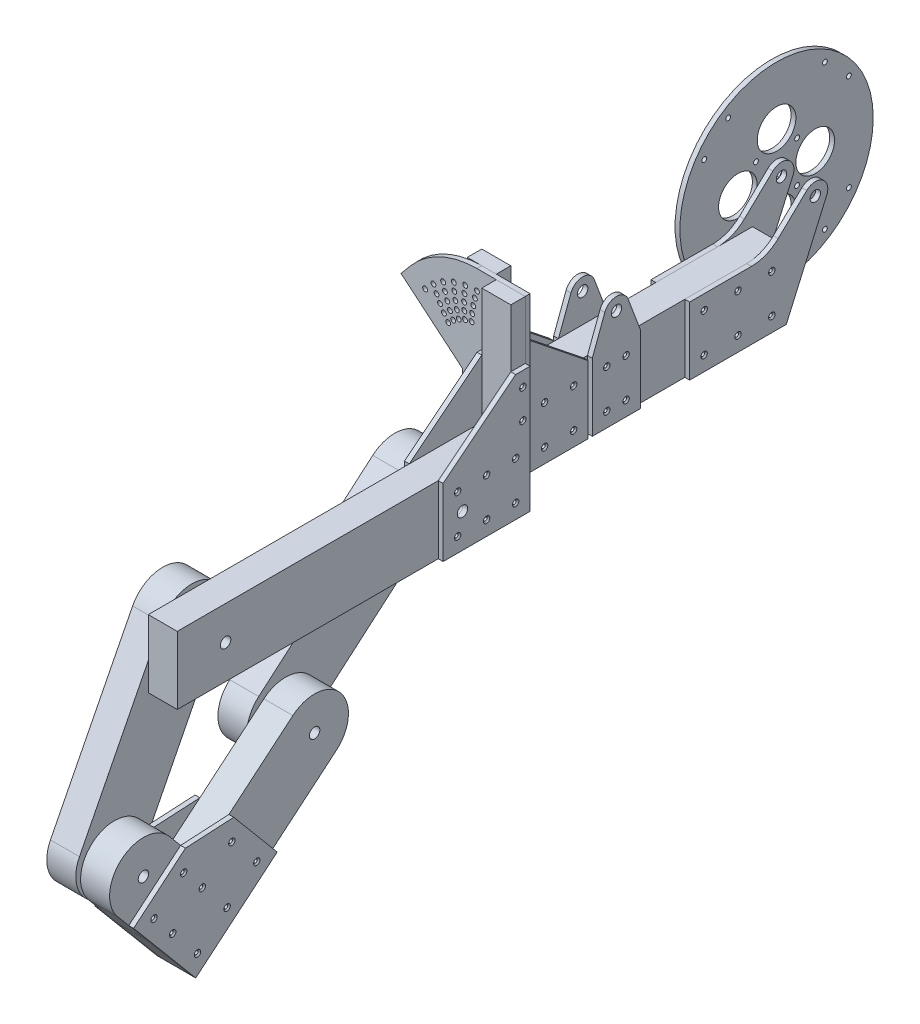
SolidWorks part; units mm, degrees
material "6061-T6 (SS)"
ref_plane "Front Plane" through (0, 0, 0) normal (0, 0, 1) x (1, 0, 0)
ref_plane "Top Plane" through (0, 0, 0) normal (0, 1, 0) x (1, 0, 0)
ref_plane "Right Plane" through (0, 0, 0) normal (1, 0, 0) x (0, 0, -1)
sketch "Sketch1" plane through (0, 0, 0) normal (1, 0, 0) x (0, 0, -1)
  line L1 (7.1857, 0) -> (3.5929, 6.223)
  line L2 (3.5929, 6.223) -> (-3.5929, 6.223)
  line L3 (-3.5929, 6.223) -> (-7.1857, 0)
  line L4 (-7.1857, 0) -> (-3.5929, -6.223)
  line L5 (-3.5929, -6.223) -> (3.5929, -6.223)
  line L6 (3.5929, -6.223) -> (7.1857, 0)
  circle A0 centre (0, 0) radius 127
  circle A2 centre (0, 50.8) radius 25.4
  circle A3 centre (50.8, 0) radius 25.4
  circle A4 centre (0, -50.8) radius 25.4
  circle A5 centre (-50.8, 0) radius 25.4
  circle A7 centre (0, 0) radius 203.2 construction
  circle A8 centre (0, 0) radius 6.223 construction
  point P14 (0, 0)
  dimension "D1" = 254
  dimension "D2" = 25.4
  dimension "D3" = 4
  dimension "2" = 50.8
  dimension "D4" = 12.446
  dimension "D5" = 406.4
extrude "Boss-Extrude1" add sketch "Sketch1" along normal blind 6.35
sketch "Sketch3" plane through (6.35, 0, 0) normal (1, 0, 0) x (0, 0, -1)
  line L0 (-26.9408, -26.9408) -> (26.9408, 26.9408) construction
  line L1 (-26.9408, 26.9408) -> (26.9408, -26.9408) construction
  line L2 (-63.5, 95.0381) -> (0, 0) construction
  line L3 (0, 0) -> (63.5, 95.0381) construction
  circle A0 centre (-26.9408, 26.9408) radius 3.175
  circle A1 centre (26.9408, 26.9408) radius 3.175
  circle A2 centre (26.9408, -26.9408) radius 3.175
  circle A3 centre (-26.9408, -26.9408) radius 3.175
  circle A4 centre (-63.5, 95.0381) radius 3.175
  circle A5 centre (63.5, 95.0381) radius 3.175
  circle A6 centre (95.0381, 63.5) radius 3.175
  circle A7 centre (95.0381, -63.5) radius 3.175
  circle A8 centre (63.5, -95.0381) radius 3.175
  circle A9 centre (-63.5, -95.0381) radius 3.175
  circle A10 centre (-95.0381, -63.5) radius 3.175
  circle A11 centre (-95.0381, 63.5) radius 3.175
  point P29 (0, 0)
  dimension "D1" = 6.35
  dimension "D2" = 76.2
  dimension "D3" = 127
  dimension "D4" = 114.3
  dimension "D5" = 4
extrude "Cut-Extrude1" cut sketch "Sketch3" against normal blind 6.35
ref_plane "Plane1" through (6.477, 0, 0) normal (1, 0, 0) x (0, 0, -1)
sketch "Sketch4" plane through (6.477, 0, 0) normal (1, 0, 0) x (0, 0, -1)
  line L0 (-38.1, -127) -> (-165.1, -127)
  line L1 (-38.1, -38.1) -> (-235.8684, -38.1) construction
  line L2 (-38.1, -38.1) -> (-38.1, -127) construction
  line L3 (-38.1, -127) -> (-235.8684, -127) construction
  line L5 (-165.1, -127) -> (-165.1, -38.1)
  line L6 (-165.1, -38.1) -> (-83.89, -38.1)
  line L7 (-48.7683, -24.0029) -> (-11.3212, 11.8309)
  line L8 (-38.1, -127) -> (14.9832, -6.6063)
  circle A0 centre (0, 0) radius 6.85
  arc A1 (14.9832, -6.6063) -> (-11.3212, 11.8309) centre (0, 0) ccw
  arc A2 (-83.89, -38.1) -> (-48.7683, -24.0029) centre (-83.89, 12.7) ccw
  point P18 (-63.5, -38.1)
  dimension "D1" = 13.7
  dimension "D5" = 9.525
  dimension "D8" = 50.8
  dimension "D2" = 127
  dimension "D3" = 38.1
  dimension "D4" = 38.1
  dimension "D6" = 101.6
  dimension "D7" = 88.9
extrude "Boss-Extrude2" add sketch "Sketch4" along normal blind 6.35 separate body
ref_plane "Plane2" through (0, 0, 38.1) normal (0, 0, 1) x (1, 0, 0)
sketch "Sketch7" plane through (0, 0, 38.1) normal (0, 0, 1) x (1, 0, 0)
  line L1 (12.827, -127) -> (50.927, -127)
  line L2 (12.827, -127) -> (12.827, -38.1)
  line L3 (12.827, -38.1) -> (50.927, -38.1)
  line L4 (50.927, -127) -> (50.927, -38.1)
  dimension "D1" = 38.1
extrude "Boss-Extrude3" add sketch "Sketch7" along normal blind 374.65 separate body
ref_plane "Plane3" through (31.877, 0, 0) normal (1, 0, 0) x (0, 0, -1)
hole_wizard "CSK for #8 Flat Head Machine Screw (100)5" positions "Sketch38" profile "Sketch39" countersink size "#8" standard "ANSI Inch"
sketch "Sketch38" plane through (6.477, 0, 0) normal (-1, 0, 0) x (0, 0, 1)
  line L0 (146.05, -107.95) -> (146.05, -127) construction
  line L1 (165.1, -127) -> (38.1, -127) construction
  line L3 (146.05, -107.95) -> (165.1, -107.95) construction
  line L4 (165.1, -38.1) -> (165.1, -127) construction
  line L6 (57.15, -57.15) -> (57.15, -38.1) construction
  line L8 (83.89, -38.1) -> (165.1, -38.1) construction
  line L9 (57.15, -57.15) -> (38.1, -57.15) construction
  line L11 (146.05, -107.95) -> (101.6, -107.95) construction
  line L12 (101.6, -107.95) -> (57.15, -107.95) construction
  point P0 (146.05, -57.15)
  point P2 (146.05, -107.95)
  point P4 (101.6, -107.95)
  point P6 (57.15, -107.95)
  point P8 (101.6, -57.15)
  point P10 (57.15, -57.15)
  dimension "D1" = 19.05
sketch "Sketch39" plane through (6.477, -57.15, 146.05) normal (0, 1, 0) x (0, 0, 1)
  line L0 (0, 0) -> (0, 7.7007)
  line L1 (0, 7.7007) -> (2.2479, 6.35)
  line L2 (2.2479, 6.35) -> (2.2479, 1.6518)
  line L3 (2.2479, 1.6518) -> (4.2164, 0)
  line L5 (4.2164, 0) -> (0, 0)
  line L6 (-2.2479, 1.6518) -> (-4.2164, 0) construction
  line L10 (0, 7.7007) -> (-2.2479, 6.35) construction
  line L11 (0, -6.35) -> (0, 107.95) construction
  dimension "Hole Dia." = 4.4958
  dimension "Hole Depth" = 6.35
  dimension "Near C'Sink Dia." = 8.4328
  dimension "Near C'Sink Angle" = 100
  dimension "Drill Angle" = 118
mirror "Mirror1" about plane through (31.877, 0, 0) normal (1, 0, 0) of bodies 131 104
sketch "Sketch8" plane through (0, -38.1, 0) normal (0, 1, 0) x (1, 0, 0)
  line L0 (12.827, -412.75) -> (12.827, -38.1) construction
  line L1 (50.927, -412.75) -> (12.827, -412.75)
  line L2 (50.927, -412.75) -> (50.927, -393.7)
  line L3 (50.927, -393.7) -> (12.827, -393.7)
  line L4 (12.827, -412.75) -> (12.827, -393.7)
  dimension "D1" = 19.05
extrude "Boss-Extrude4" add sketch "Sketch8" along normal blind 152.4 separate body
sketch "Sketch9" plane through (12.827, 0, 0) normal (-1, 0, 0) x (0, 0, 1)
  line L0 (412.75, 38.1) -> (412.75, -127)
  line L1 (412.75, 114.3) -> (412.75, -38.1) construction
  line L2 (412.75, -127) -> (298.45, -127)
  line L3 (298.45, -127) -> (298.45, -38.1)
  line L4 (412.75, -38.1) -> (38.1, -38.1) construction
  line L5 (298.45, -38.1) -> (393.7, 38.1)
  line L6 (393.7, 114.3) -> (393.7, -38.1) construction
  line L7 (393.7, 38.1) -> (412.75, 38.1)
  dimension "D1" = 114.3
extrude "Boss-Extrude5" add sketch "Sketch9" along normal blind 6.35 separate body
hole_wizard "CSK for #8 Flat Head Machine Screw (100)1" positions "Sketch12" profile "Sketch11" countersink size "#8" standard "ANSI Inch"
sketch "Sketch12" plane through (6.477, 0, 0) normal (-1, 0, 0) x (0, 0, 1)
  line L0 (403.225, -19.05) -> (403.225, 19.05) construction
  line L2 (393.7, 19.05) -> (412.75, 19.05) construction
  line L4 (412.75, 114.3) -> (412.75, -38.1) construction
  line L5 (393.7, 114.3) -> (393.7, -38.1) construction
  line L6 (403.225, 19.05) -> (403.225, 38.1) construction
  line L7 (412.75, 38.1) -> (393.7, 38.1) construction
  line L9 (393.7, -107.95) -> (393.7, -57.15) construction
  line L10 (393.7, -57.15) -> (355.6, -57.15) construction
  line L11 (355.6, -57.15) -> (317.5, -57.15) construction
  line L13 (355.6, -57.15) -> (355.6, -107.95) construction
  line L15 (317.5, -57.15) -> (317.5, -107.95) construction
  line L16 (317.5, -107.95) -> (355.6, -107.95) construction
  line L17 (355.6, -107.95) -> (393.7, -107.95) construction
  line L19 (412.75, -127) -> (412.75, 38.1) construction
  line L20 (298.45, -127) -> (412.75, -127) construction
  line L21 (393.7, -107.95) -> (393.7, -127) construction
  line L23 (393.7, -107.95) -> (412.75, -107.95) construction
  line L25 (317.5, -57.15) -> (317.5, -38.1) construction
  line L27 (412.75, -38.1) -> (38.1, -38.1) construction
  line L28 (317.5, -57.15) -> (298.45, -57.15) construction
  line L29 (298.45, -38.1) -> (298.45, -127) construction
  point P0 (403.225, 19.05)
  point P2 (403.225, -19.05)
  point P4 (393.7, -57.15)
  point P6 (393.7, -107.95)
  point P8 (355.6, -107.95)
  point P10 (355.6, -57.15)
  point P12 (317.5, -57.15)
  point P14 (317.5, -107.95)
  dimension "D1" = 19.05
  dimension "D2" = 38.1
  dimension "D3" = 19.05
  dimension "D4" = 19.05
sketch "Sketch11" plane through (6.477, 19.05, 403.225) normal (0, 1, 0) x (0, 0, 1)
  line L0 (0, 0) -> (0, 8.9453)
  line L1 (0, 8.9453) -> (2.2479, 7.5946)
  line L2 (2.2479, 7.5946) -> (2.2479, 1.6518)
  line L3 (2.2479, 1.6518) -> (4.2164, 0)
  line L5 (4.2164, 0) -> (0, 0)
  line L6 (-2.2479, 1.6518) -> (-4.2164, 0) construction
  line L10 (0, 8.9453) -> (-2.2479, 7.5946) construction
  line L11 (0, -6.35) -> (0, 107.95) construction
  dimension "Hole Dia." = 4.4958
  dimension "Hole Depth" = 7.5946
  dimension "Near C'Sink Dia." = 8.4328
  dimension "Near C'Sink Angle" = 100
  dimension "Drill Angle" = 118
mirror "Mirror2" about plane through (31.877, 0, 0) normal (1, 0, 0) of bodies 109 111
sketch "Sketch13" plane through (0, 0, 412.75) normal (0, 0, 1) x (1, 0, 0)
  line L0 (12.827, 0) -> (50.927, 0) construction
  line L1 (12.827, 114.3) -> (12.827, -38.1) construction
  line L2 (50.927, -127) -> (50.927, 38.1) construction
  circle A0 centre (31.877, 0) radius 3.175
  circle A1 centre (31.877, 88.9) radius 3.175
  dimension "D1" = 6.35
  dimension "D2" = 88.9
extrude "Cut-Extrude3" cut sketch "Sketch13" against normal up to next (19.05 mm away)
sketch "Sketch16" plane through (0, 0, 412.75) normal (0, 0, 1) x (1, 0, 0)
  line L0 (31.877, 88.9) -> (31.877, 79.375) construction
  line L1 (31.877, 79.375) -> (31.877, 69.85) construction
  line L2 (31.877, 69.85) -> (31.877, 60.325) construction
  line L3 (31.877, 60.325) -> (31.877, 50.8) construction
  circle A0 centre (31.877, 79.375) radius 3.175
  circle A1 centre (31.877, 69.85) radius 3.175
  circle A2 centre (31.877, 60.325) radius 3.175
  circle A3 centre (31.877, 50.8) radius 3.175
  circle A5 centre (31.877, 88.9) radius 3.175 construction
  dimension "D1" = 9.525
extrude "Cut-Extrude5" cut sketch "Sketch16" against normal up to next (19.05 mm away)
sketch "Sketch14" plane through (0, 0, 412.75) normal (0, 0, 1) x (1, 0, 0)
  line L1 (57.277, -38.1) -> (12.827, -38.1)
  line L2 (12.827, 114.3) -> (50.927, 114.3) construction
  line L3 (-55.6819, 73.4706) -> (31.877, 0) construction
  line L4 (31.877, 79.375) -> (31.877, 0) construction
  line L5 (31.877, 0) -> (29.1069, 79.3266) construction
  line L6 (31.877, 0) -> (29.1069, 79.3266) construction
  line L7 (31.877, 0) -> (15.374, 77.6405) construction
  line L8 (31.877, 0) -> (27.0045, 69.6798) construction
  line L9 (31.877, 69.85) -> (31.877, 0) construction
  line L10 (-21.2352, 58.9871) -> (31.877, 0) construction
  line L11 (25.5713, 59.9945) -> (31.877, 0) construction
  line L12 (31.877, 60.325) -> (31.877, 0) construction
  line L13 (24.807, 50.3056) -> (31.877, 0) construction
  line L14 (31.877, 0) -> (31.877, 50.8) construction
  line L15 (31.877, 0) -> (27.0045, 69.6798) construction
  line L16 (31.877, 0) -> (14.9788, 67.7752) construction
  line L17 (31.877, 0) -> (25.5713, 59.9945) construction
  line L18 (31.877, 0) -> (15.2492, 57.9881) construction
  line L19 (31.877, 0) -> (24.807, 50.3056) construction
  line L20 (31.877, 0) -> (16.1789, 48.3137) construction
  line L21 (31.877, 0) -> (31.877, 88.9) construction
  line L22 (31.877, 0) -> (16.4397, 87.5494) construction
  line L23 (12.827, -127) -> (12.827, 38.1) construction
  line L24 (12.827, 114.3) -> (12.827, -38.1) construction
  line L25 (31.877, 114.3) -> (50.927, 114.3)
  line L26 (-55.6819, 73.4706) -> (-67.927, 58.8775)
  line L27 (-67.927, 58.8775) -> (12.827, -8.8832)
  line L28 (12.827, -8.8832) -> (12.827, -38.1)
  line L30 (95.377, 114.3) -> (95.377, -38.1)
  line L33 (57.277, -127) -> (57.277, 38.1) construction
  line L34 (50.927, -38.1) -> (12.827, -38.1) construction
  line L35 (57.277, -38.1) -> (95.377, -38.1)
  line L37 (95.377, 114.3) -> (50.927, 114.3)
  line L39 (50.927, 114.3) -> (12.827, 114.3) construction
  line L40 (50.927, 114.3) -> (50.927, -38.1) construction
  arc A0 (31.877, 114.3) -> (-55.6819, 73.4706) centre (31.877, 0) ccw
  circle A1 centre (31.877, 0) radius 3.175 construction
  circle A2 centre (31.877, 88.9) radius 3.175
  circle A3 centre (31.877, 88.9) radius 3.175 construction
  circle A8 centre (29.1069, 79.3266) radius 3.175
  circle A9 centre (31.877, 79.375) radius 3.175 construction
  circle A10 centre (15.374, 77.6405) radius 3.175
  circle A11 centre (2.1426, 73.5952) radius 3.175
  circle A12 centre (-10.1853, 67.3138) radius 3.175
  circle A13 centre (-21.2352, 58.9871) radius 3.175
  circle A14 centre (27.0045, 69.6798) radius 3.175
  circle A15 centre (25.5713, 59.9945) radius 3.175
  circle A16 centre (24.807, 50.3056) radius 3.175
  circle A17 centre (31.877, 69.85) radius 3.175 construction
  circle A18 centre (14.9788, 67.7752) radius 3.175
  circle A19 centre (3.4664, 63.8112) radius 3.175
  circle A20 centre (-7.1826, 57.9083) radius 3.175
  circle A21 centre (-16.6449, 50.2459) radius 3.175
  circle A22 centre (15.2492, 57.9881) radius 3.175
  circle A23 centre (5.4323, 54.2198) radius 3.175
  circle A24 centre (-3.5811, 48.804) radius 3.175
  circle A25 centre (-11.5172, 41.9053) radius 3.175
  circle A26 centre (16.1789, 48.3137) radius 3.175
  circle A27 centre (8.0278, 44.8537) radius 3.175
  circle A28 centre (0.6014, 40.0309) radius 3.175
  circle A29 centre (-5.8748, 33.9918) radius 3.175
  circle A30 centre (16.4397, 87.5494) radius 3.175
  circle A31 centre (1.4714, 83.5387) radius 3.175
  circle A32 centre (-12.573, 76.9897) radius 3.175
  circle A33 centre (-25.2668, 68.1014) radius 3.175
  circle A34 centre (-36.2244, 57.1438) radius 3.175
  circle A35 centre (31.877, 0) radius 3.175
  point P28 (31.877, 0)
  dimension "D3" = 2
  dimension "D5" = 10
  dimension "D6" = 4
  dimension "D7" = 6
  dimension "D8" = 8
  dimension "D10" = 10
  dimension "D12" = 10
  dimension "D14" = 10
  dimension "D15" = 10
  dimension "D4" = 5
  dimension "D9" = 5
  dimension "D11" = 5
  dimension "D13" = 5
  dimension "D2" = 6
extrude "Boss-Extrude6" add sketch "Sketch14" along normal blind 6.35 separate body
hole_wizard "CSK for #8 Flat Head Machine Screw (100)2" positions "Sketch19" profile "Sketch20" countersink size "#8" standard "ANSI Inch"
sketch "Sketch19" plane through (0, 0, 412.75) normal (0, 0, -1) x (-1, 0, 0)
  line L0 (-95.377, -12.7) -> (-57.277, -12.7) construction
  line L1 (-95.377, -38.1) -> (-95.377, 114.3) construction
  line L2 (-57.277, -127) -> (-57.277, 38.1) construction
  line L4 (-76.327, -12.7) -> (-76.327, -38.1) construction
  line L5 (-12.827, -38.1) -> (-95.377, -38.1) construction
  line L7 (-76.327, -12.7) -> (-76.327, 12.7) construction
  line L8 (-76.327, 12.7) -> (-76.327, 38.1) construction
  line L9 (-76.327, 38.1) -> (-76.327, 63.5) construction
  line L10 (-76.327, 63.5) -> (-76.327, 88.9) construction
  line L11 (-76.327, 88.9) -> (-76.327, 114.3) construction
  line L12 (-95.377, 114.3) -> (-31.877, 114.3) construction
  point P9 (-76.327, -12.7)
  point P16 (-76.327, 12.7)
  point P17 (-76.327, 38.1)
  point P19 (-76.327, 63.5)
  point P21 (-76.327, 88.9)
sketch "Sketch20" plane through (76.327, 88.9, 412.75) normal (1, 0, 0) x (0, 1, 0)
  line L0 (0, 0) -> (0, 7.7007)
  line L1 (0, 7.7007) -> (2.2479, 6.35)
  line L2 (2.2479, 6.35) -> (2.2479, 1.6518)
  line L3 (2.2479, 1.6518) -> (4.2164, 0)
  line L5 (4.2164, 0) -> (0, 0)
  line L6 (-2.2479, 1.6518) -> (-4.2164, 0) construction
  line L10 (0, 7.7007) -> (-2.2479, 6.35) construction
  line L11 (0, -6.35) -> (0, 107.95) construction
  dimension "Hole Dia." = 4.4958
  dimension "Hole Depth" = 6.35
  dimension "Near C'Sink Dia." = 8.4328
  dimension "Near C'Sink Angle" = 100
  dimension "Drill Angle" = 118
sketch "Sketch21" plane through (0, 0, 419.1) normal (0, 0, 1) x (1, 0, 0)
  line L0 (12.827, -38.1) -> (95.377, -38.1) construction
  line L1 (95.377, 114.3) -> (57.277, 114.3)
  line L2 (95.377, 114.3) -> (95.377, -38.1)
  line L3 (95.377, -38.1) -> (57.277, -38.1)
  line L4 (57.277, 114.3) -> (57.277, -38.1)
  line L5 (12.827, -127) -> (50.927, -127) construction
extrude "Boss-Extrude7" add sketch "Sketch21" along normal blind 19.05 separate body
ref_plane "Plane4" through (0, 0, 415.925) normal (0, 0, 1) x (1, 0, 0)
sketch "Sketch23" plane through (31.877, 0, 0) normal (1, 0, 0) x (0, 0, -1)
  line L0 (-263.6019, 31.144) -> (-3.8591, 50.8544)
  line L1 (-263.6019, -31.144) -> (-3.8591, -50.8544)
  circle A0 centre (0, 0) radius 51.0007 construction
  circle A1 centre (-261.2386, 0) radius 31.2336 construction
  arc A2 (-263.6019, 31.144) -> (-263.6019, -31.144) centre (-261.2386, 0) ccw
  arc A3 (-3.8591, 50.8544) -> (-3.8591, -50.8544) centre (0, 0) cw
  dimension "D1" = 102.0013
  dimension "D2" = 62.4671
sketch "Sketch24" plane through (50.927, 0, 0) normal (1, 0, 0) x (0, 0, -1)
  line L0 (-292.9886, -127) -> (-229.4886, -127)
  line L1 (-412.75, -127) -> (-38.1, -127) construction
  line L2 (-292.9886, -127) -> (-292.9886, -38.1)
  line L3 (-412.75, -38.1) -> (-38.1, -38.1) construction
  line L4 (-292.9886, -38.1) -> (-276.574, 5.7417)
  line L5 (-245.9032, 5.7417) -> (-229.4886, -38.1)
  line L6 (-229.4886, -38.1) -> (-229.4886, -127)
  circle A0 centre (-261.2386, 0) radius 6.85
  arc A2 (-263.6019, 31.144) -> (-263.6019, -31.144) centre (-261.2386, 0) ccw construction
  circle A3 centre (-261.2386, 0) radius 16.375 construction
  arc A4 (-276.574, 5.7417) -> (-245.9032, 5.7417) centre (-261.2386, 0) cw
  point P16 (-261.2386, -127)
  dimension "D1" = 13.7
  dimension "D2" = 9.525
  dimension "2.5" = 63.5
extrude "Boss-Extrude11" add sketch "Sketch24" along normal blind 6.35 separate body
hole_wizard "CSK for #8 Flat Head Machine Screw (100)3" positions "Sketch25" profile "Sketch26" countersink size "#8" standard "ANSI Inch"
sketch "Sketch25" plane through (57.277, 0, 0) normal (1, 0, 0) x (0, 0, -1)
  line L0 (-273.9386, -57.15) -> (-273.9386, -107.95) construction
  line L1 (-273.9386, -107.95) -> (-248.5386, -107.95) construction
  line L3 (-273.9386, -107.95) -> (-273.9386, -127) construction
  line L4 (-292.9886, -127) -> (-229.4886, -127) construction
  line L6 (-273.9386, -107.95) -> (-292.9886, -107.95) construction
  line L7 (-292.9886, -38.1) -> (-292.9886, -127) construction
  line L9 (-248.5386, -57.15) -> (-248.5386, -38.1) construction
  line L11 (-248.5386, -57.15) -> (-229.4886, -57.15) construction
  line L12 (-229.4886, -127) -> (-229.4886, -38.1) construction
  line L14 (-412.75, -38.1) -> (-38.1, -38.1) construction
  point P0 (-248.5386, -57.15)
  point P2 (-248.5386, -107.95)
  point P4 (-273.9386, -107.95)
  point P6 (-273.9386, -57.15)
  dimension "D1" = 19.05
sketch "Sketch26" plane through (57.277, -57.15, 248.5386) normal (0, 1, 0) x (0, 0, -1)
  line L0 (0, 0) -> (0, 7.7007)
  line L1 (0, 7.7007) -> (2.2479, 6.35)
  line L2 (2.2479, 6.35) -> (2.2479, 1.6518)
  line L3 (2.2479, 1.6518) -> (4.2164, 0)
  line L5 (4.2164, 0) -> (0, 0)
  line L6 (-2.2479, 1.6518) -> (-4.2164, 0) construction
  line L10 (0, 7.7007) -> (-2.2479, 6.35) construction
  line L11 (0, -6.35) -> (0, 107.95) construction
  dimension "Hole Dia." = 4.4958
  dimension "Hole Depth" = 6.35
  dimension "Near C'Sink Dia." = 8.4328
  dimension "Near C'Sink Angle" = 100
  dimension "Drill Angle" = 118
mirror "Mirror4" about plane through (31.877, 0, 0) normal (1, 0, 0) of bodies 123 124
sketch "Sketch27" plane through (57.277, 0, 0) normal (-1, 0, 0) x (0, 0, 1)
  line L0 (419.1, 38.1) -> (419.1, -127)
  line L1 (419.1, 114.3) -> (419.1, -38.1) construction
  line L2 (419.1, -127) -> (533.4, -127)
  line L3 (533.4, -127) -> (533.4, -38.1)
  line L4 (533.4, -38.1) -> (438.15, 38.1)
  line L5 (438.15, 114.3) -> (438.15, -38.1) construction
  line L6 (438.15, 38.1) -> (419.1, 38.1)
  line L7 (412.75, 38.1) -> (393.7, 38.1) construction
  line L8 (298.45, -127) -> (412.75, -127) construction
  line L9 (412.75, -38.1) -> (38.1, -38.1) construction
extrude "Boss-Extrude12" add sketch "Sketch27" along normal blind 6.35 separate body
hole_wizard "CSK for #8 Flat Head Machine Screw (100)4" positions "Sketch29" profile "Sketch30" countersink size "#8" standard "ANSI Inch"
sketch "Sketch29" plane through (50.927, 0, 0) normal (-1, 0, 0) x (0, 0, 1)
  line L0 (419.1, 19.05) -> (438.15, 19.05) construction
  line L1 (419.1, 38.1) -> (419.1, -127) construction
  line L3 (438.15, 114.3) -> (438.15, -38.1) construction
  line L4 (438.15, 38.1) -> (419.1, 38.1) construction
  line L5 (438.15, -107.95) -> (438.15, -127) construction
  line L6 (419.1, -127) -> (533.4, -127) construction
  line L8 (438.15, -107.95) -> (419.1, -107.95) construction
  line L10 (514.35, -57.15) -> (533.4, -57.15) construction
  line L11 (533.4, -127) -> (533.4, -38.1) construction
  line L13 (514.35, -57.15) -> (514.35, -38.1) construction
  line L15 (438.15, -107.95) -> (476.25, -107.95) construction
  line L16 (476.25, -107.95) -> (514.35, -107.95) construction
  point P0 (428.625, 19.05)
  point P2 (428.625, -19.05)
  point P4 (438.15, -57.15)
  point P6 (438.15, -107.95)
  point P8 (476.25, -57.15)
  point P10 (476.25, -107.95)
  point P12 (514.35, -57.15)
  point P14 (514.35, -107.95)
  dimension "D1" = 19.05
  dimension "D2" = 38.1
  dimension "D3" = 19.05
sketch "Sketch30" plane through (50.927, 19.05, 428.625) normal (0, 1, 0) x (0, 0, 1)
  line L0 (0, 0) -> (0, 7.7007)
  line L1 (0, 7.7007) -> (2.2479, 6.35)
  line L2 (2.2479, 6.35) -> (2.2479, 1.6518)
  line L3 (2.2479, 1.6518) -> (4.2164, 0)
  line L5 (4.2164, 0) -> (0, 0)
  line L6 (-2.2479, 1.6518) -> (-4.2164, 0) construction
  line L10 (0, 7.7007) -> (-2.2479, 6.35) construction
  line L11 (0, -6.35) -> (0, 107.95) construction
  dimension "Hole Dia." = 4.4958
  dimension "Hole Depth" = 6.35
  dimension "Near C'Sink Dia." = 8.4328
  dimension "Near C'Sink Angle" = 100
  dimension "Drill Angle" = 118
sketch "Sketch33" plane through (0, 0, 419.1) normal (0, 0, 1) x (1, 0, 0)
  line L1 (57.277, -38.1) -> (95.377, -38.1)
  line L2 (57.277, -38.1) -> (57.277, -127)
  line L3 (57.277, -127) -> (95.377, -127)
  line L4 (95.377, -38.1) -> (95.377, -127)
  dimension "D1" = 38.1
  dimension "D2" = 88.9
extrude "Boss-Extrude13" add sketch "Sketch33" along normal blind 457.2 separate body
ref_plane "Plane5" through (76.327, 0, 0) normal (1, 0, 0) x (0, 0, -1)
mirror "Mirror5" about plane through (76.327, 0, 0) normal (1, 0, 0) of bodies 127 128
sketch "Sketch40" plane through (12.827, 0, 0) normal (-1, 0, 0) x (0, 0, 1)
  circle A0 centre (57.15, -57.15) radius 1.3891
  circle A1 centre (101.6, -57.15) radius 1.3891
  circle A2 centre (57.15, -107.95) radius 1.3891
  circle A3 centre (101.6, -107.95) radius 1.3891
  circle A4 centre (146.05, -107.95) radius 1.3891
  circle A5 centre (146.05, -57.15) radius 1.3891
  circle A6 centre (248.5386, -57.15) radius 1.3891
  circle A7 centre (248.5386, -107.95) radius 1.3891
  circle A8 centre (273.9386, -57.15) radius 1.3891
  circle A9 centre (273.9386, -107.95) radius 1.3891
  circle A10 centre (317.5, -57.15) radius 1.3891
  circle A11 centre (317.5, -107.95) radius 1.3891
  circle A12 centre (355.6, -107.95) radius 1.3891
  circle A13 centre (393.7, -57.15) radius 1.3891
  circle A14 centre (393.7, -107.95) radius 1.3891
  circle A15 centre (355.6, -57.15) radius 1.3891
  circle A16 centre (403.225, -19.05) radius 1.3891
  circle A17 centre (403.225, 19.05) radius 1.3891
  circle A18 centre (146.05, -107.95) radius 2.2479 construction
  circle A19 centre (57.15, -57.15) radius 2.2479 construction
  circle A20 centre (101.6, -107.95) radius 2.2479 construction
  dimension "D1" = 2.7781
extrude "Cut-Extrude6" cut sketch "Sketch40" against normal blind 12.7
mirror "Mirror7" about plane through (31.877, 0, 0) normal (1, 0, 0) of "Cut-Extrude6"
sketch "Sketch42" plane through (95.377, 0, 0) normal (1, 0, 0) x (0, 0, -1)
  circle A0 centre (-428.625, 19.05) radius 1.3891
  circle A1 centre (-428.625, -19.05) radius 1.3891
  circle A2 centre (-438.15, -57.15) radius 1.3891
  circle A3 centre (-438.15, -107.95) radius 1.3891
  circle A4 centre (-476.25, -107.95) radius 1.3891
  circle A5 centre (-476.25, -57.15) radius 1.3891
  circle A6 centre (-514.35, -57.15) radius 1.3891
  circle A7 centre (-514.35, -107.95) radius 1.3891
  circle A8 centre (-476.25, -107.95) radius 2.2479 construction
  dimension "D1" = 2.7781
extrude "Cut-Extrude7" cut sketch "Sketch42" against normal blind 12.7
mirror "Mirror8" about plane through (76.327, 0, 0) normal (1, 0, 0) of "Cut-Extrude7"
sketch "Sketch43" plane through (31.877, 0, 0) normal (1, 0, 0) x (0, 0, -1)
  line L0 (-476.714, -77.1417) -> (-539.286, -87.9583) construction
  line L1 (-438.15, -57.15) -> (-438.15, -107.95) construction
  circle A0 centre (-508, -82.55) radius 6.85
  point P2 (-438.15, -82.55)
  point P6 (-508, -82.55)
  dimension "D2" = 13.7
  dimension "D1" = 508
  dimension "D3" = 63.5
extrude "Cut-Extrude8" cut sketch "Sketch43" along normal through all
sketch "Sketch44" plane through (57.277, 0, 0) normal (-1, 0, 0) x (0, 0, 1)
  circle A0 centre (812.8, -82.55) radius 6.85
  circle A1 centre (508, -82.55) radius 6.85 construction
  point P3 (508, -82.55)
  dimension "D1" = 812.8
extrude "Cut-Extrude9" cut sketch "Sketch44" against normal through all
sketch "Sketch46" plane through (57.277, 0, 0) normal (-1, 0, 0) x (0, 0, 1)
  circle A0 centre (812.8, -82.55) radius 7.9375
  circle A1 centre (812.8, -82.55) radius 15.875
  dimension "D1" = 31.75
  dimension "D2" = 15.875
extrude "Boss-Extrude14" add sketch "Sketch46" along normal blind 6.35 separate body
sketch "Sketch47" plane through (50.927, 0, 0) normal (-1, 0, 0) x (0, 0, 1)
  line L0 (508, -82.55) -> (695.8783, -243.8952) construction
  line L1 (812.8, -82.55) -> (920.7384, -294.8065) construction
  line L2 (695.8783, -243.8952) -> (852.9005, -375.6525) construction
  line L3 (852.9005, -375.6525) -> (920.7384, -294.8065) construction
  line L4 (695.8783, -243.8952) -> (832.756, -243.8952) construction
  line L5 (479.0406, -116.2717) -> (666.9189, -277.6169)
  line L6 (773.1788, -102.6985) -> (881.1172, -314.955)
  line L7 (536.9594, -48.8283) -> (724.8377, -210.1734)
  line L8 (852.4212, -62.4015) -> (960.3596, -274.658)
  circle A0 centre (508, -82.55) radius 6.85
  circle A1 centre (508, -82.55) radius 6.85 construction
  circle A2 centre (695.8783, -243.8952) radius 6.85
  arc A3 (536.9594, -48.8283) -> (479.0406, -116.2717) centre (508, -82.55) ccw
  arc A4 (666.9189, -277.6169) -> (724.8377, -210.1734) centre (695.8783, -243.8952) ccw
  arc A5 (773.1788, -102.6985) -> (852.4212, -62.4015) centre (812.8, -82.55) cw
  arc A6 (881.1172, -314.955) -> (960.3596, -274.658) centre (920.7384, -294.8065) ccw
  circle A7 centre (920.7384, -294.8065) radius 6.85
  circle A8 centre (812.8, -82.55) radius 6.85 construction
  circle A9 centre (812.8, -82.55) radius 6.85
  dimension "D1" = 247.65
  dimension "D2" = 238.125
  dimension "D3" = 105.537
  dimension "D4" = 204.978
  dimension "D5" = 40
  dimension "D6" = 44.45
extrude "Boss-Extrude15" add sketch "Sketch47" along normal blind 38.1 separate body
sketch "Sketch48" plane through (50.927, 0, 0) normal (1, 0, 0) x (0, 0, -1)
  circle A0 centre (-695.8783, -243.8952) radius 7.9375
  circle A1 centre (-695.8783, -243.8952) radius 15.875
  circle A2 centre (-920.7384, -294.8065) radius 15.875
  circle A3 centre (-920.7384, -294.8065) radius 7.9375
  dimension "D1" = 15.875
  dimension "D2" = 31.75
extrude "Boss-Extrude16" add sketch "Sketch48" along normal blind 6.35 separate body
sketch "Sketch49" plane through (57.277, 0, 0) normal (1, 0, 0) x (0, 0, -1)
  line L0 (-915.5231, -370.1737) -> (-724.4502, -209.8445)
  line L2 (-667.3064, -277.9459) -> (-858.3793, -438.2751)
  line L3 (-858.3793, -438.2751) -> (-915.5231, -370.1737)
  line L4 (-695.8783, -243.8952) -> (-852.9005, -375.6525) construction
  line L5 (-852.9005, -375.6525) -> (-920.7384, -294.8065) construction
  circle A0 centre (-695.8783, -243.8952) radius 6.85
  circle A1 centre (-695.8783, -243.8952) radius 6.85 construction
  arc A2 (-724.4502, -209.8445) -> (-667.3064, -277.9459) centre (-695.8783, -243.8952) cw
  dimension "D1" = 44.45
  dimension "D3" = 88.9
extrude "Boss-Extrude17" add sketch "Sketch49" along normal blind 38.1 separate body
sketch "Sketch50" plane through (57.277, 0, 0) normal (1, 0, 0) x (0, 0, -1)
  line L0 (-915.5231, -370.1737) -> (-954.7891, -323.3784)
  line L1 (-915.5231, -370.1737) -> (-858.3793, -438.2751) construction
  line L2 (-886.6877, -266.2346) -> (-847.4218, -313.0299)
  line L3 (-847.4218, -313.0299) -> (-915.5231, -370.1737)
  line L4 (-724.4502, -209.8445) -> (-915.5231, -370.1737) construction
  line L5 (-852.9005, -375.6525) -> (-920.7384, -294.8065) construction
  circle A0 centre (-920.7384, -294.8065) radius 6.85 construction
  circle A1 centre (-920.7384, -294.8065) radius 6.85
  arc A2 (-954.7891, -323.3784) -> (-886.6877, -266.2346) centre (-920.7384, -294.8065) cw
extrude "Boss-Extrude18" add sketch "Sketch50" along normal blind 38.1 separate body
sketch "Sketch51" plane through (57.277, 0, 0) normal (-1, 0, 0) x (0, 0, 1)
  line L0 (940.0133, -340.9875) -> (858.3793, -438.2751)
  line L1 (954.7891, -323.3784) -> (915.5231, -370.1737) construction
  line L2 (858.3793, -438.2751) -> (751.3629, -348.4777)
  line L3 (858.3793, -438.2751) -> (667.3064, -277.9459) construction
  line L4 (751.3629, -348.4777) -> (808.5067, -280.3763)
  line L5 (724.4502, -209.8445) -> (915.5231, -370.1737) construction
  line L6 (808.5067, -280.3763) -> (871.912, -283.8436)
  line L7 (847.4218, -313.0299) -> (886.6877, -266.2346) construction
  line L8 (871.912, -283.8436) -> (940.0133, -340.9875)
  line L9 (915.5231, -370.1737) -> (847.4218, -313.0299) construction
  dimension "D1" = 139.7
  dimension "D2" = 38.1
extrude "Boss-Extrude19" add sketch "Sketch51" along normal blind 6.35 separate body
hole_wizard "CSK for #8 Flat Head Machine Screw (100)6" positions "Sketch52" profile "Sketch53" countersink size "#8" standard "ANSI Inch"
sketch "Sketch52" plane through (50.927, 0, 0) normal (-1, 0, 0) x (0, 0, 1)
  line L0 (856.0313, -411.4368) -> (843.7862, -426.03) construction
  line L1 (751.3629, -348.4777) -> (858.3793, -438.2751) construction
  line L3 (856.0313, -411.4368) -> (870.6244, -423.6819) construction
  line L4 (858.3793, -438.2751) -> (940.0133, -340.9875) construction
  line L5 (810.8548, -307.2146) -> (823.0999, -292.6214) construction
  line L7 (796.2616, -294.9695) -> (810.8548, -307.2146) construction
  line L8 (808.5067, -280.3763) -> (751.3629, -348.4777) construction
  line L9 (724.4502, -209.8445) -> (915.5231, -370.1737) construction
  line L10 (874.26, -310.6819) -> (859.6669, -298.4368) construction
  line L12 (913.1751, -343.3355) -> (927.7682, -355.5806) construction
  line L14 (847.4218, -313.0299) -> (886.6877, -266.2346) construction
  line L15 (778.2012, -346.1296) -> (856.0313, -411.4368) construction
  line L17 (810.8548, -307.2146) -> (888.6849, -372.5218) construction
  point P0 (874.26, -310.6819)
  point P2 (913.1751, -343.3355)
  point P4 (888.6849, -372.5218)
  point P6 (856.0313, -411.4368)
  point P8 (849.7698, -339.8682)
  point P10 (817.1162, -378.7832)
  point P12 (778.2012, -346.1296)
  point P14 (810.8548, -307.2146)
  dimension "D1" = 19.05
  dimension "D2" = 19.05
sketch "Sketch53" plane through (50.927, -310.6819, 874.26) normal (0, 1, 0) x (0, 0, 1)
  line L0 (0, 0) -> (0, 7.7007)
  line L1 (0, 7.7007) -> (2.2479, 6.35)
  line L2 (2.2479, 6.35) -> (2.2479, 1.6518)
  line L3 (2.2479, 1.6518) -> (4.2164, 0)
  line L5 (4.2164, 0) -> (0, 0)
  line L6 (-2.2479, 1.6518) -> (-4.2164, 0) construction
  line L10 (0, 7.7007) -> (-2.2479, 6.35) construction
  line L11 (0, -6.35) -> (0, 107.95) construction
  dimension "Hole Dia." = 4.4958
  dimension "Hole Depth" = 6.35
  dimension "Near C'Sink Dia." = 8.4328
  dimension "Near C'Sink Angle" = 100
  dimension "Drill Angle" = 118
mirror "Mirror9" about plane through (76.327, 0, 0) normal (1, 0, 0)
sketch "Sketch54" plane through (57.277, 0, 0) normal (-1, 0, 0) x (0, 0, 1)
  circle A0 centre (810.8548, -307.2146) radius 1.3891
  circle A1 centre (778.2012, -346.1296) radius 1.3891
  circle A2 centre (817.1162, -378.7832) radius 1.3891
  circle A3 centre (856.0313, -411.4368) radius 1.3891
  circle A4 centre (888.6849, -372.5218) radius 1.3891
  circle A5 centre (849.7698, -339.8682) radius 1.3891
  circle A6 centre (874.26, -310.6819) radius 1.3891
  circle A7 centre (913.1751, -343.3355) radius 1.3891
  dimension "D1" = 2.7781
extrude "Cut-Extrude10" cut sketch "Sketch54" against normal blind 12.7
mirror "Mirror10" about plane through (76.327, 0, 0) normal (1, 0, 0) of "Cut-Extrude10"
sketch "Sketch55" plane through (0, 0, 419.1) normal (0, 0, -1) x (-1, 0, 0)
  circle A0 centre (-76.327, -12.7) radius 1.3891
  circle A1 centre (-76.327, 12.7) radius 1.3891
  circle A2 centre (-76.327, 38.1) radius 1.3891
  circle A3 centre (-76.327, 63.5) radius 1.3891
  circle A4 centre (-76.327, 88.9) radius 1.3891
  dimension "D1" = 2.7781
extrude "Cut-Extrude11" cut sketch "Sketch55" against normal blind 12.7
equation "\"D1@Sketch23\"=.350*1/sin(180/36)"
equation "\"D2@Sketch23\"=.350*1/sin(180/22)"
equation "\"D3@Sketch23\"=88*.350"
